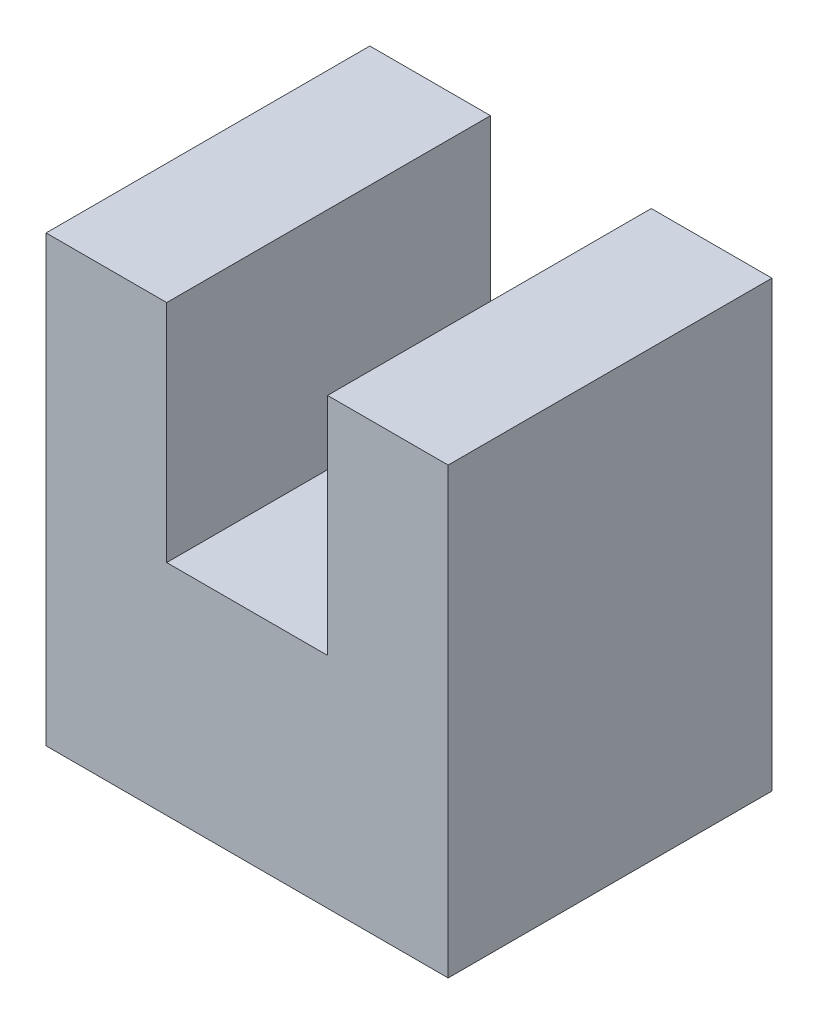
SolidWorks part; units mm, degrees
ref_plane "Front Plane" through (0, 0, 0) normal (0, 0, 1) x (1, 0, 0)
ref_plane "Top Plane" through (0, 0, 0) normal (0, 1, 0) x (1, 0, 0)
ref_plane "Right Plane" through (0, 0, 0) normal (1, 0, 0) x (0, 0, -1)
sketch "Sketch1" plane through (0, 0, 0) normal (0, 0, 1) x (1, 0, 0)
  line L0 (-1, 4.762) -> (-1, 1.962)
  line L1 (2.5, -0.762) -> (-2.5, -0.762)
  line L2 (2.5, -0.762) -> (2.5, 0.762)
  line L3 (2.5, 0.762) -> (-2.5, 0.762)
  line L4 (-2.5, -0.762) -> (-2.5, 0.762)
  line L5 (2.5, -0.762) -> (-2.5, 0.762) construction
  line L6 (2.5, 0.762) -> (-2.5, -0.762) construction
  line L8 (-2.5, 0.762) -> (-2.5, 4.762)
  line L9 (-2.5, 4.762) -> (2.5, 4.762)
  line L10 (2.5, 0.762) -> (2.5, 4.762)
  line L11 (-1, 1.962) -> (1, 1.962)
  line L12 (1, 1.962) -> (1, 4.762)
  line L13 (0, 0) -> (0, 7.1762) construction
  point P1 (0, 0)
  dimension "D1" = 1.524
  dimension "D2" = 5
  dimension "D3" = 4
  dimension "D4" = 2
  dimension "D5" = 2.8
extrude "Boss-Extrude1" add sketch "Sketch1" along normal blind 4.0259 contours L12 L11 L0 L9 L8 L3 L10 | L4 L1 L2 L3
